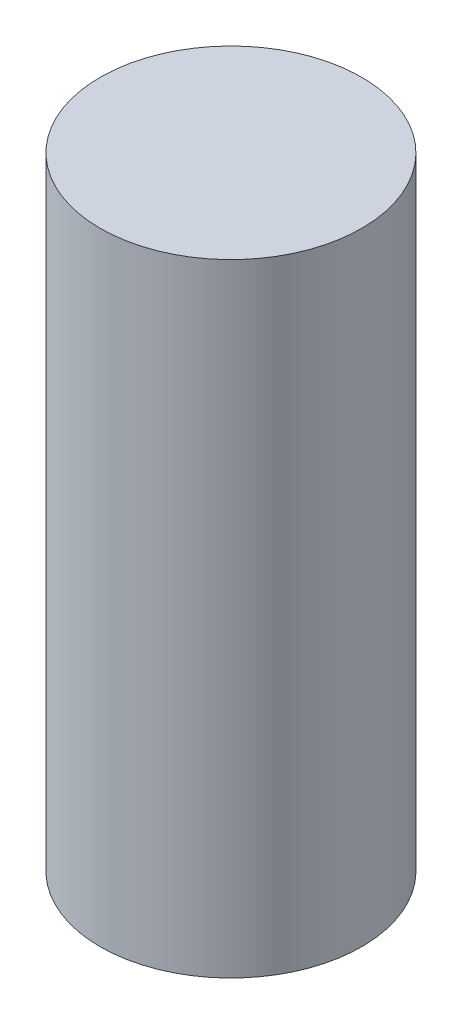
SolidWorks part; units mm, degrees
ref_plane "Front Plane" through (0, 0, 0) normal (0, 0, 1) x (1, 0, 0)
ref_plane "Top Plane" through (0, 0, 0) normal (0, 1, 0) x (1, 0, 0)
ref_plane "Right Plane" through (0, 0, 0) normal (1, 0, 0) x (0, 0, -1)
sketch "Sketch2" plane through (0, 0, 0) normal (0, 1, 0) x (1, 0, 0)
  circle A0 centre (0, 0) radius 10.6807
  dimension "D1" = 21.3614
extrude "Boss-Extrude1" add sketch "Sketch2" along normal blind 50.8
